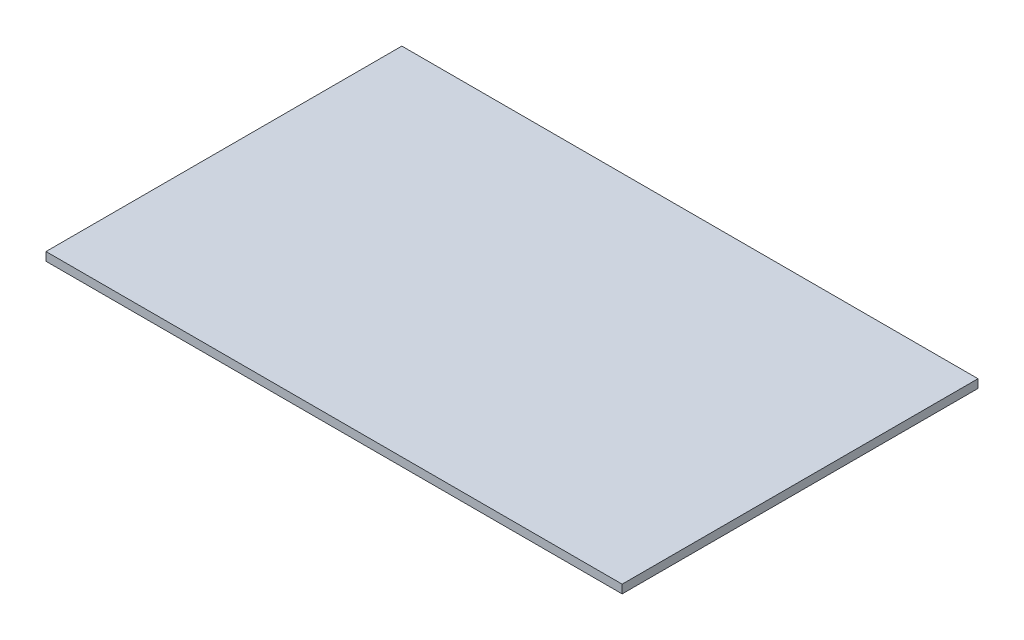
SolidWorks part; units mm, degrees
material "ABS"
ref_plane "Front Plane" through (0, 0, 0) normal (0, 0, 1) x (1, 0, 0)
ref_plane "Top Plane" through (0, 0, 0) normal (0, 1, 0) x (1, 0, 0)
ref_plane "Right Plane" through (0, 0, 0) normal (1, 0, 0) x (0, 0, -1)
sketch "Sketch1" plane through (0, 0, 0) normal (0, 1, 0) x (1, 0, 0)
  line L1 (-15.936, -7.5696) -> (18.064, -7.5696)
  line L2 (-15.936, -7.5696) -> (-15.936, 13.4304)
  line L3 (-15.936, 13.4304) -> (18.064, 13.4304)
  line L4 (18.064, -7.5696) -> (18.064, 13.4304)
extrude "Boss-Extrude1" add sketch "Sketch1" along normal blind 0.5
